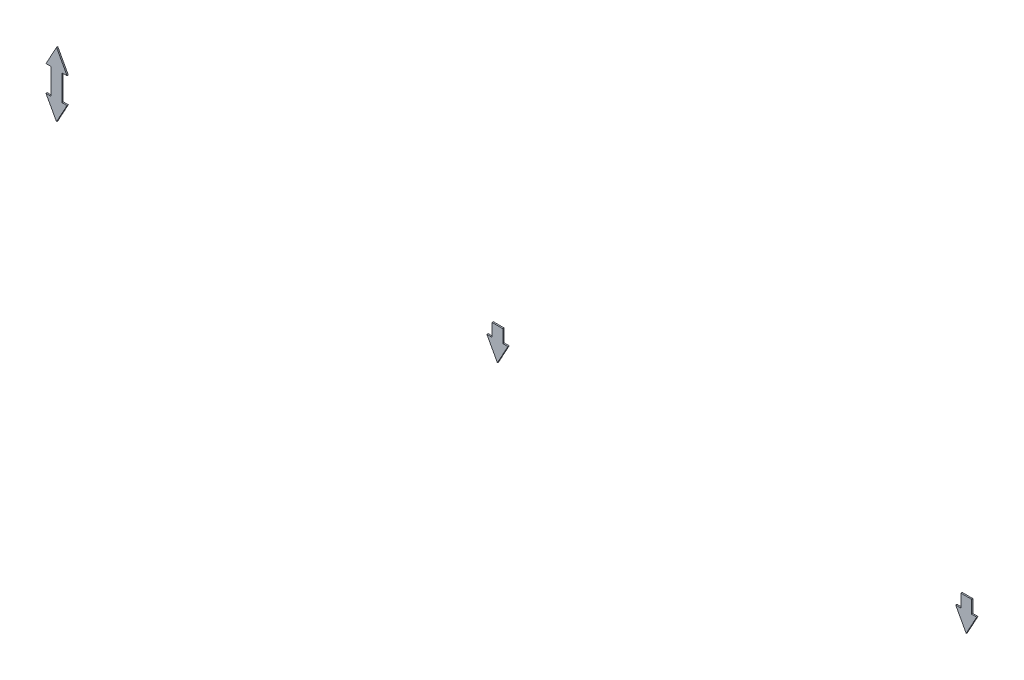
SolidWorks part; units mm, degrees
ref_plane "Front Plane" through (0, 0, 0) normal (0, 0, 1) x (1, 0, 0)
ref_plane "Top Plane" through (0, 0, 0) normal (0, 1, 0) x (1, 0, 0)
ref_plane "Right Plane" through (0, 0, 0) normal (1, 0, 0) x (0, 0, -1)
sketch "Sketch1" plane through (0, 0, 0) normal (0, 0, 1) x (1, 0, 0)
  line L0 (-10.9488, 1225.5306) -> (7339.0512, 1225.5306) construction
  line L1 (7339.0512, 1225.5306) -> (7339.0512, 13046.142) construction
  line L2 (7464.0512, 925.5306) -> (7464.0512, 1525.5306)
  line L3 (7464.0512, 1525.5306) -> (7583.4735, 1525.5306)
  line L4 (7583.4735, 1525.5306) -> (7339.0512, 1974.5305)
  line L5 (7339.0512, 476.5307) -> (7339.0512, 1974.5305) construction
  line L6 (7094.629, 1525.5306) -> (7339.0512, 1974.5305)
  line L7 (7214.0512, 1525.5306) -> (7094.629, 1525.5306)
  line L8 (7214.0512, 925.5306) -> (7214.0512, 1525.5306)
  line L9 (17590.5486, 1498.6506) -> (17590.5486, -2032.5553) construction
  line L10 (28490.5486, 1498.6506) -> (28490.5486, -3649.407) construction
  line L11 (17715.5486, 1198.6506) -> (17715.5486, 1498.6506)
  line L12 (17465.5486, 1198.6506) -> (17465.5486, 1498.6506)
  line L13 (28734.9709, 1198.6506) -> (28490.5486, 749.6507)
  line L14 (17465.5486, 1498.6506) -> (17715.5486, 1498.6506)
  line L15 (17346.1264, 1198.6506) -> (7339.0512, 1225.5306) construction
  line L16 (28365.5486, 1198.6506) -> (28365.5486, 1498.6506)
  line L17 (28615.5486, 1198.6506) -> (28734.9709, 1198.6506)
  line L18 (28615.5486, 1198.6506) -> (28615.5486, 1498.6506)
  line L19 (17715.5486, 1498.6506) -> (17590.5486, 1498.6506) construction
  line L20 (28365.5486, 1198.6506) -> (28246.1264, 1198.6506)
  line L24 (28246.1264, 1198.6506) -> (28490.5486, 749.6507)
  line L25 (28365.5486, 1498.6506) -> (28615.5486, 1498.6506)
  line L28 (28615.5486, 1498.6506) -> (28490.5486, 1498.6506) construction
  line L29 (7339.0512, 1225.5306) -> (7339.0512, -10595.0807) construction
  line L30 (7214.0512, 925.5306) -> (7094.629, 925.5306)
  line L31 (7094.629, 925.5306) -> (7339.0512, 476.5307)
  line L32 (7583.4735, 925.5306) -> (7339.0512, 476.5307)
  line L33 (7464.0512, 925.5306) -> (7583.4735, 925.5306)
  line L34 (17465.5486, 1198.6506) -> (17346.1264, 1198.6506)
  line L35 (17346.1264, 1198.6506) -> (17590.5486, 749.6507)
  line L36 (17715.5486, 1198.6506) -> (17834.9709, 1198.6506)
  line L37 (17834.9709, 1198.6506) -> (17590.5486, 749.6507)
extrude "Boss-Extrude1" add sketch "Sketch1" along normal blind 30
